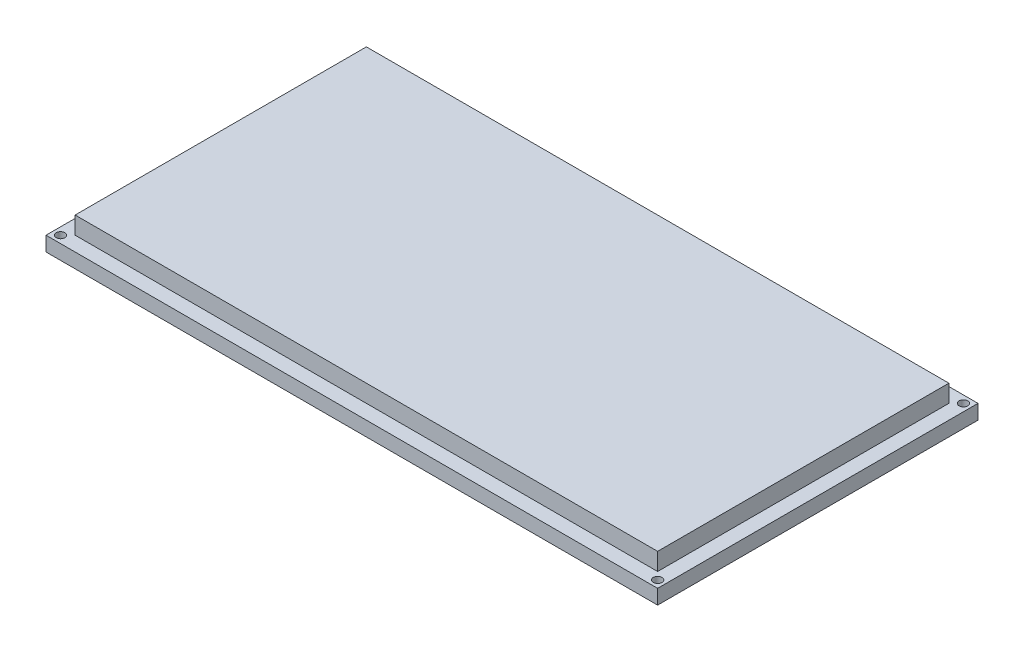
SolidWorks part; units mm, degrees
ref_plane "Front Plane" through (0, 0, 0) normal (0, 0, 1) x (1, 0, 0)
ref_plane "Top Plane" through (0, 0, 0) normal (0, 1, 0) x (1, 0, 0)
ref_plane "Right Plane" through (0, 0, 0) normal (1, 0, 0) x (0, 0, -1)
sketch "Sketch1" plane through (0, 0, 0) normal (0, 1, 0) x (1, 0, 0)
  line L1 (-105, 55) -> (105, 55)
  line L2 (-105, 55) -> (-105, -55)
  line L3 (-105, -55) -> (105, -55)
  line L4 (105, 55) -> (105, -55)
  dimension "D1" = 110
  dimension "D2" = 210
  dimension "D3" = 105
  dimension "D4" = 55
extrude "Top" add sketch "Sketch1" along normal blind 5
sketch "Sketch2" plane through (0, 5, 0) normal (0, 1, 0) x (1, 0, 0)
  line L1 (-100, -50) -> (100, -50)
  line L2 (-100, -50) -> (-100, 50)
  line L3 (-100, 50) -> (100, 50)
  line L4 (100, -50) -> (100, 50)
  dimension "D1" = 100
  dimension "D2" = 200
  dimension "D3" = 100
  dimension "D4" = 50
extrude "Bottom" add sketch "Sketch2" along normal blind 6
sketch "Sketch4" plane through (0, 5, 0) normal (0, 1, 0) x (1, 0, 0)
  line L0 (-105, 55) -> (-105, -55) construction
  line L1 (-105, -55) -> (105, -55) construction
  circle A0 centre (-102.5, -52.5) radius 1.5
  dimension "D1" = 2.5
  dimension "D3" = 3
  dimension "D2" = 2.5
extrude "Hole" cut sketch "Sketch4" against normal up to next
pattern_linear "Hole-Pattern" count 2 spacing 105 along (0, 0, -1) count 2 spacing 205 along (1, 0, 0) of "Hole"
